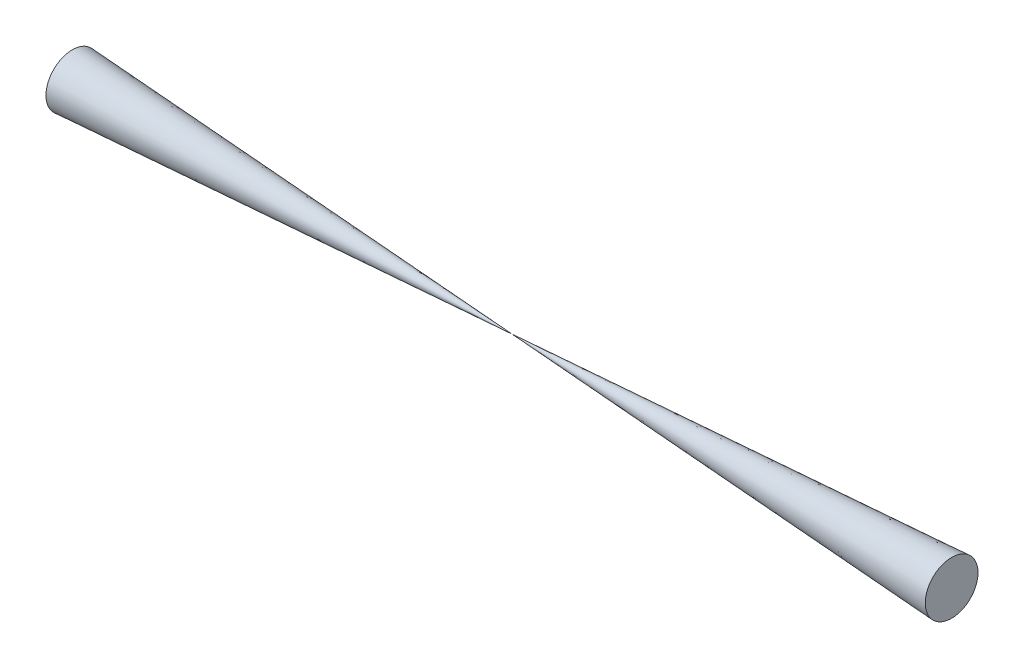
SolidWorks part; units mm, degrees
ref_plane "前视基准面" through (0, 0, 0) normal (0, 0, 1) x (1, 0, 0)
ref_plane "上视基准面" through (0, 0, 0) normal (0, 1, 0) x (1, 0, 0)
ref_plane "右视基准面" through (0, 0, 0) normal (1, 0, 0) x (0, 0, -1)
sketch "草图1" plane through (0, 0, 0) normal (0, 1, 0) x (1, 0, 0)
  line L0 (0, 0) -> (0, 0.01)
  line L1 (0, 0.01) -> (200, 12)
  line L2 (200, 12) -> (200, 0)
  line L3 (200, 0) -> (0, 0)
  dimension "D1" = 0.01
  dimension "D2" = 12
  dimension "D3" = 200
revolve "旋转1" add sketch "草图1" angle 360 about L3
mirror "镜向1" about plane through (0, 0, 0) normal (-1, 0, 0) of "旋转1"
sketch "草图2" plane through (0, 0, 0) normal (0, 1, 0) x (1, 0, 0)
  line L0 (0, 2.5197) -> (0, -2.4532) construction
  line L1 (-0.9583, 0) -> (1.2658, 0) construction
